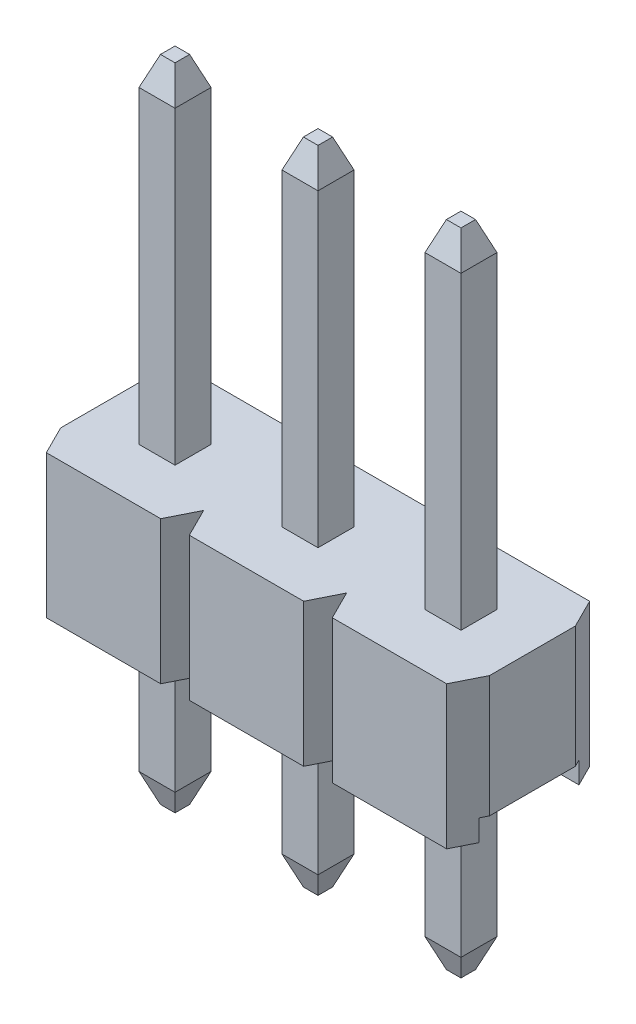
SolidWorks part; units mm, degrees
ref_plane "Front Plane" through (0, 0, 0) normal (0, 0, 1) x (1, 0, 0)
ref_plane "Top Plane" through (0, 0, 0) normal (0, 1, 0) x (1, 0, 0)
ref_plane "Right Plane" through (0, 0, 0) normal (1, 0, 0) x (0, 0, -1)
sketch "Sketch1" plane through (0, 0, 0) normal (0, 1, 0) x (1, 0, 0)
  line L1 (0, 0) -> (2.54, 0)
  line L2 (0, 0) -> (0, 2.54)
  line L3 (0, 2.54) -> (2.54, 2.54)
  line L4 (2.54, 0) -> (2.54, 2.54)
  dimension "D1" = 2.54
  dimension "D2" = 2.54
extrude "Main Body" add sketch "Sketch1" along normal blind 2.54
sketch "Sketch3" plane through (0, 0, 0) normal (-1, 0, 0) x (0, 0, 1)
  line L0 (-2.54, 0) -> (0, 0) construction
  line L1 (-2.159, 0) -> (-0.381, 0)
  line L2 (-2.159, 0) -> (-2.159, 0.381)
  line L3 (-2.159, 0.381) -> (-0.381, 0.381)
  line L4 (-0.381, 0) -> (-0.381, 0.381)
  line L5 (-2.54, 0) -> (-2.159, 0) construction
  line L6 (-0.381, 0) -> (0, 0) construction
  dimension "D1" = 0.381
extrude "Cut-Extrude1" cut sketch "Sketch3" against normal through all
sketch "Sketch4" plane through (0, 2.54, 0) normal (0, 1, 0) x (1, 0, 0)
  line L0 (0, 2.54) -> (0, 2.032)
  line L1 (0, 2.54) -> (0, 0) construction
  line L2 (0, 2.032) -> (0.254, 2.54)
  line L3 (2.54, 2.54) -> (0, 2.54) construction
  line L4 (0.254, 2.54) -> (0, 2.54)
  line L5 (2.54, 2.54) -> (2.286, 2.54)
  line L6 (2.286, 2.54) -> (2.54, 2.032)
  line L7 (2.54, 0) -> (2.54, 2.54) construction
  line L8 (2.54, 2.032) -> (2.54, 2.54)
  line L9 (2.54, 0) -> (2.286, 0)
  line L10 (0, 0) -> (2.54, 0) construction
  line L11 (2.286, 0) -> (2.54, 0.508)
  line L12 (2.54, 0.508) -> (2.54, 0)
  line L14 (0, 0) -> (0, 0.508)
  line L15 (0, 0.508) -> (0.254, 0)
  line L16 (0.254, 0) -> (0, 0)
  line M1 (0, 2.54) -> (0, 0)
  line M2 (0, 0) -> (2.54, 0)
  line M3 (2.54, 0) -> (2.54, 2.54)
  line M4 (2.54, 2.54) -> (0, 2.54)
  dimension "D1" = 0.254
  dimension "D2" = 0.508
extrude "Cut-Extrude2" cut sketch "Sketch4" against normal through all contours L2 M1 M4 | L6 M4 M3 | L15 M1 M2 | L9 L11 L12
pattern_linear "Body Pattern" count 3 spacing 2.54 along (-1, 0, 0) of "Main Body", "Cut-Extrude1", "Cut-Extrude2"
sketch "Sketch2" plane through (0, 2.54, 0) normal (0, 1, 0) x (1, 0, 0)
  line L0 (1.27, 2.54) -> (1.27, 1.59) construction
  line L1 (0.95, 0.95) -> (1.59, 0.95)
  line L2 (0.95, 0.95) -> (0.95, 1.59)
  line L3 (0.95, 1.59) -> (1.59, 1.59)
  line L4 (1.59, 0.95) -> (1.59, 1.59)
  line L6 (2.286, 2.54) -> (0.254, 2.54) construction
  line L8 (1.27, 0.95) -> (1.27, 0) construction
  line L9 (0.254, 0) -> (2.286, 0) construction
  dimension "D1" = 0.64
extrude "Pin" add sketch "Sketch2" along normal blind 6 and the other way offset from surface (5.54 mm away) 3 other way up to face at (1.27, 0, -0.1905)
chamfer "Chamfer1" distance 0.508 distance2 0.1905 4 edges at (0.95, 8.54, -1.27) (1.27, 8.54, -1.59) (1.59, 8.54, -1.27) (1.27, 8.54, -0.95)
chamfer "Chamfer2" distance 0.1905 distance2 0.508 4 edges at (1.27, -3, -1.59) (1.59, -3, -1.27) (1.27, -3, -0.95) (0.95, -3, -1.27)
pattern_linear "Pin Pattern" count 3 spacing 2.54 along (-1, 0, 0) of "Pin", "Chamfer1", "Chamfer2"
ref_plane "Плоскость1" through (-1.27, 0, 0) normal (1, 0, 0) x (0, 0, -1)
ref_plane "Плоскость2" through (0, 0, -1.27) normal (0, 0, 1) x (1, 0, 0)
